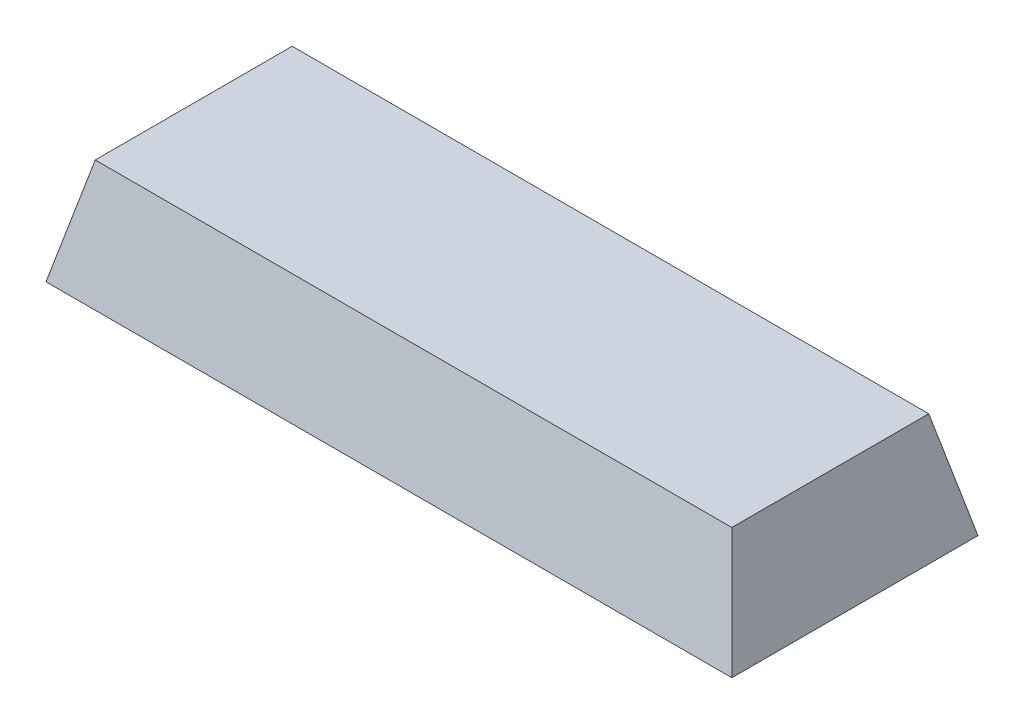
SolidWorks part; units mm, degrees
ref_plane "Front Plane" through (0, 0, 0) normal (0, 0, 1) x (1, 0, 0)
ref_plane "Top Plane" through (0, 0, 0) normal (0, 1, 0) x (1, 0, 0)
ref_plane "Right Plane" through (0, 0, 0) normal (1, 0, 0) x (0, 0, -1)
sketch "Sketch1" plane through (0, 0, 0) normal (0, 1, 0) x (1, 0, 0)
  line L1 (0, 0) -> (19.5, 0)
  line L2 (0, 0) -> (0, 7)
  line L3 (0, 7) -> (19.5, 7)
  line L4 (19.5, 0) -> (19.5, 7)
  dimension "D1" = 7
  dimension "D2" = 19.5
extrude "Boss-Extrude1" add sketch "Sketch1" along normal blind 3
sketch "Sketch2" plane through (0, 0, 0) normal (0, 0, 1) x (1, 0, 0)
  line L0 (0, 0) -> (0.7, 3)
  line L1 (0, 3) -> (19.5, 3) construction
  line L2 (0.7, 3) -> (0, 3)
  line L3 (0, 3) -> (0, 0)
  line L4 (19.5, 0) -> (18.8, 3)
  line L5 (18.8, 3) -> (19.5, 3)
  line L6 (19.5, 3) -> (19.5, 0)
  dimension "D1" = 0.7
  dimension "D2" = 0.7
extrude "Cut-Extrude1" cut sketch "Sketch2" against normal blind 7
sketch "Sketch3" plane through (0, 0, 0) normal (1, 0, 0) x (0, 0, -1)
  line L0 (0, 0) -> (0.7, 3)
  line L1 (7, 3) -> (0, 3) construction
  line L2 (0.7, 3) -> (0, 3)
  line L3 (0, 3) -> (0, 0)
  line L4 (7, 3) -> (6.3, 3)
  line L5 (6.3, 3) -> (7, 0)
  line L6 (7, 3) -> (7, 0)
  dimension "D1" = 0.7
  dimension "D2" = 0.7
extrude "Cut-Extrude2" cut sketch "Sketch3" along normal through all both and the other way through all
sketch "Sketch4" plane through (0, 0, 0) normal (0, -1, 0) x (1, 0, 0)
  line L0 (9.75, 0) -> (9.75, -7) construction
  line L1 (0, 0) -> (19.5, 0) construction
  line L2 (19.5, -7) -> (0, -7) construction
  line L3 (0, -3.5) -> (19.5, -3.5) construction
  line L4 (0, -7) -> (0, 0) construction
  line L5 (19.5, 0) -> (19.5, -7) construction
  circle A0 centre (9.75, -3.5) radius 1.8
  dimension "D1" = 3.6
extrude "Cut-Extrude3" cut sketch "Sketch4" against normal blind 0.8
